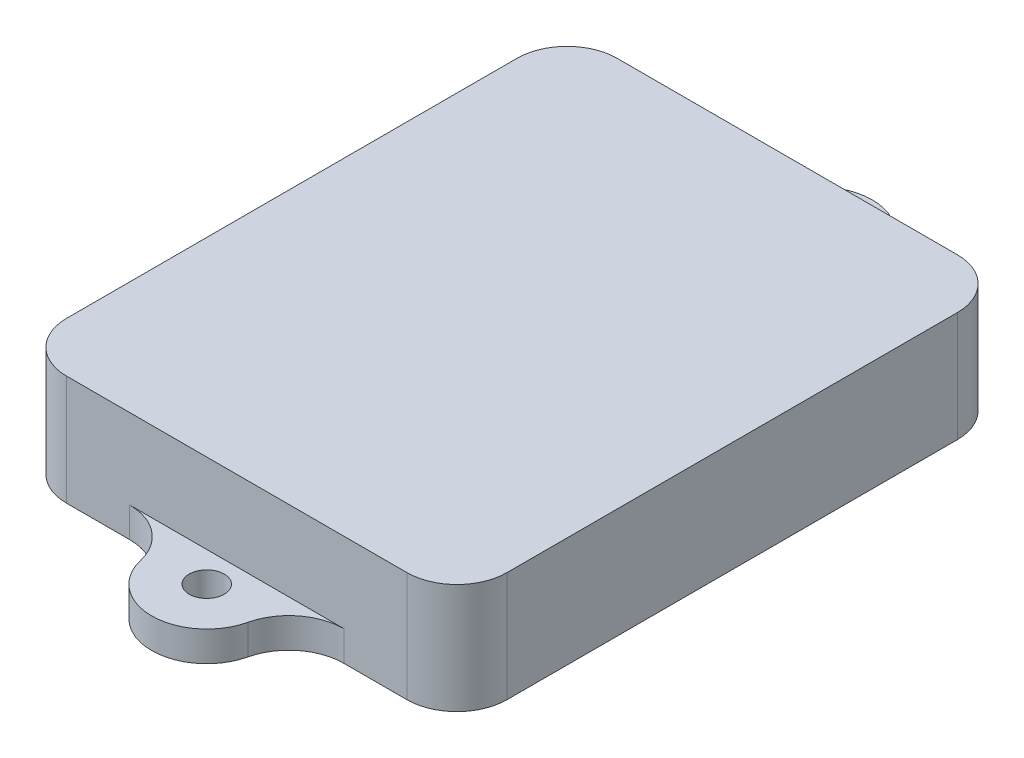
SolidWorks part; units mm, degrees
ref_plane "Front Plane" through (0, 0, 0) normal (0, 0, 1) x (1, 0, 0)
ref_plane "Top Plane" through (0, 0, 0) normal (0, 1, 0) x (1, 0, 0)
ref_plane "Right Plane" through (0, 0, 0) normal (1, 0, 0) x (0, 0, -1)
sketch "Sketch1" plane through (0, 0, 0) normal (0, 1, 0) x (1, 0, 0)
  line L0 (0, 0) -> (33.9958, 0) construction
  line L1 (17, -27.5) -> (10.7121, -27.5)
  line L2 (22, -22.5) -> (22, 22.5)
  line L3 (17, 27.5) -> (10.7121, 27.5)
  line L4 (-22, -22.5) -> (-22, 22.5)
  line L5 (22, -27.5) -> (-22, 27.5) construction
  line L6 (22, 27.5) -> (-22, -27.5) construction
  line L7 (-10.7121, -27.5) -> (-17, -27.5)
  line L8 (-10.7121, 27.5) -> (-17, 27.5)
  arc A0 (-5.3561, -31.75) -> (5.3561, -31.75) centre (0, -30.5) ccw
  arc A1 (-5.3561, -31.75) -> (-10.7121, -27.5) centre (-10.7121, -33) ccw
  arc A2 (5.3561, -31.75) -> (10.7121, -27.5) centre (10.7121, -33) cw
  arc A3 (5.3561, 31.75) -> (10.7121, 27.5) centre (10.7121, 33) ccw
  arc A4 (-5.3561, 31.75) -> (5.3561, 31.75) centre (0, 30.5) cw
  arc A5 (-5.3561, 31.75) -> (-10.7121, 27.5) centre (-10.7121, 33) cw
  arc A6 (17, -27.5) -> (22, -22.5) centre (17, -22.5) ccw
  arc A7 (-17, -27.5) -> (-22, -22.5) centre (-17, -22.5) cw
  arc A8 (22, 22.5) -> (17, 27.5) centre (17, 22.5) ccw
  arc A9 (-17, 27.5) -> (-22, 22.5) centre (-17, 22.5) ccw
  circle A10 centre (0, -30.5) radius 1.75
  circle A11 centre (0, 30.5) radius 1.75
  point P0 (0, 0)
  point P35 (0, -30.1826)
  dimension "D3" = 11
  dimension "D4" = 5
  dimension "D5" = 3.5
  dimension "D1" = 55
  dimension "D2" = 44
  dimension "D6" = 3
extrude "Boss-Extrude1" add sketch "Sketch1" along normal blind 11
sketch "Sketch2" plane through (0, 11, 0) normal (0, 1, 0) x (1, 0, 0)
  line L0 (-13.8561, -27.5) -> (13.8561, -27.5)
  line L1 (-17, -27.5) -> (-10.7121, -27.5) construction
  line L2 (10.7121, -27.5) -> (17, -27.5) construction
  line L3 (13.8561, -27.5) -> (13.8561, -36)
  line L4 (13.8561, -36) -> (-13.8561, -36)
  line L5 (-13.8561, -36) -> (-13.8561, -27.5)
  line L6 (-13.8561, 27.5) -> (13.8561, 27.5)
  line L7 (-10.7121, 27.5) -> (-17, 27.5) construction
  line L8 (17, 27.5) -> (10.7121, 27.5) construction
  line L9 (13.8561, 27.5) -> (13.8561, 36)
  line L10 (13.8561, 36) -> (-13.8561, 36)
  line L11 (-13.8561, 36) -> (-13.8561, 27.5)
  arc A0 (-5.3561, -31.75) -> (5.3561, -31.75) centre (0, -30.5) ccw construction
  arc A1 (5.3561, 31.75) -> (-5.3561, 31.75) centre (0, 30.5) ccw construction
extrude "Cut-Extrude1" cut sketch "Sketch2" against normal offset from surface (8 mm away) 3 up to face at (0, 0, 0)
